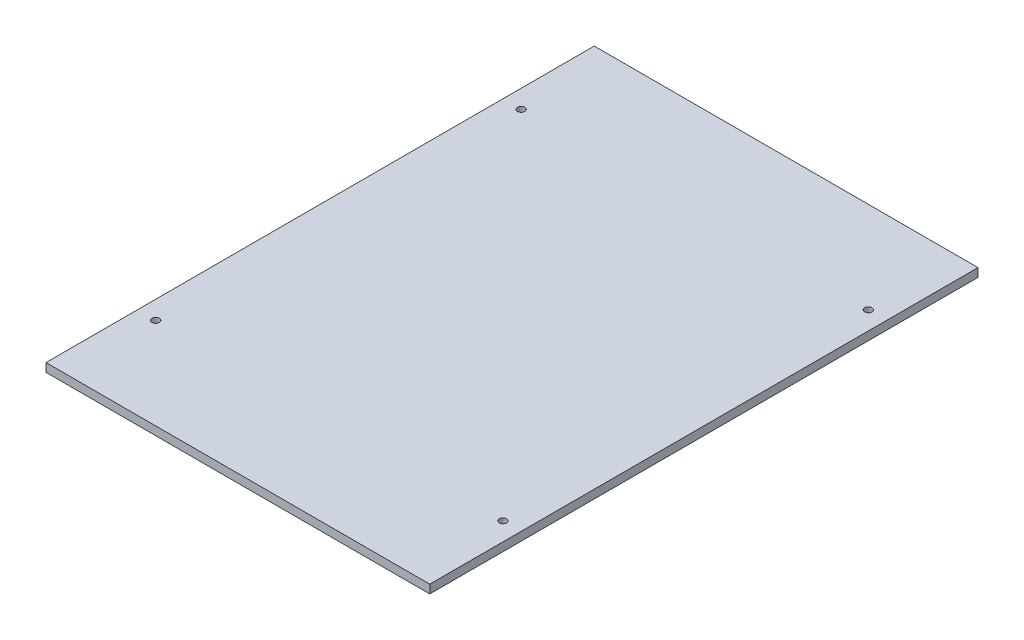
SolidWorks part; units mm, degrees
material "丙烯酸(中高冲击)"
ref_plane "Front" through (0, 0, 0) normal (0, 0, 1) x (1, 0, 0)
ref_plane "Top" through (0, 0, 0) normal (0, 1, 0) x (1, 0, 0)
ref_plane "Right" through (0, 0, 0) normal (1, 0, 0) x (0, 0, -1)
sketch "草图1" plane through (0, 0, 0) normal (0, 1, 0) x (1, 0, 0)
  line L42 (0, 0) -> (210, 0)
  line L43 (0, 0) -> (0, 300)
  line L44 (0, 300) -> (210, 300)
  line L45 (210, 0) -> (210, 300)
  dimension "D1" = 210
  dimension "D2" = 300
extrude "凸台-拉伸1" add sketch "草图1" along normal blind 4.65
fillet "圆角1" [suppressed] radius 1.5
hole_wizard "大小mm 暗销孔1" positions "草图2" profile "草图3" hole size "Ø4.0" standard "GB" end condition through all
sketch "草图2" plane through (0, 4.65, 0) normal (0, 1, 0) x (1, 0, 0)
  line L4 (0, 300) -> (0, 0) construction
  line L5 (210, 0) -> (210, 300) construction
  line L6 (210, 300) -> (0, 300) construction
  line L7 (0, 0) -> (210, 0) construction
  point P0 (10, 250)
  point P2 (10, 50)
  point P4 (200, 250)
  point P6 (200, 50)
  dimension "D1" = 10
  dimension "D2" = 10
  dimension "D3" = 50
  dimension "D4" = 50
sketch "草图3" plane through (10, 4.65, -250) normal (1, 0, 0) x (0, 0, 1)
  line L0 (0, 0) -> (0, 4.65)
  line L1 (0, 4.65) -> (2, 4.65)
  line L2 (2, 4.65) -> (2, 0)
  line L5 (2, 0) -> (0, 0)
  line L11 (0, -6.35) -> (0, 107.95) construction
  dimension "通孔孔直径" = 4
  dimension "通孔孔深度" = 4.65
fillet "圆角2" [suppressed] radius 8
